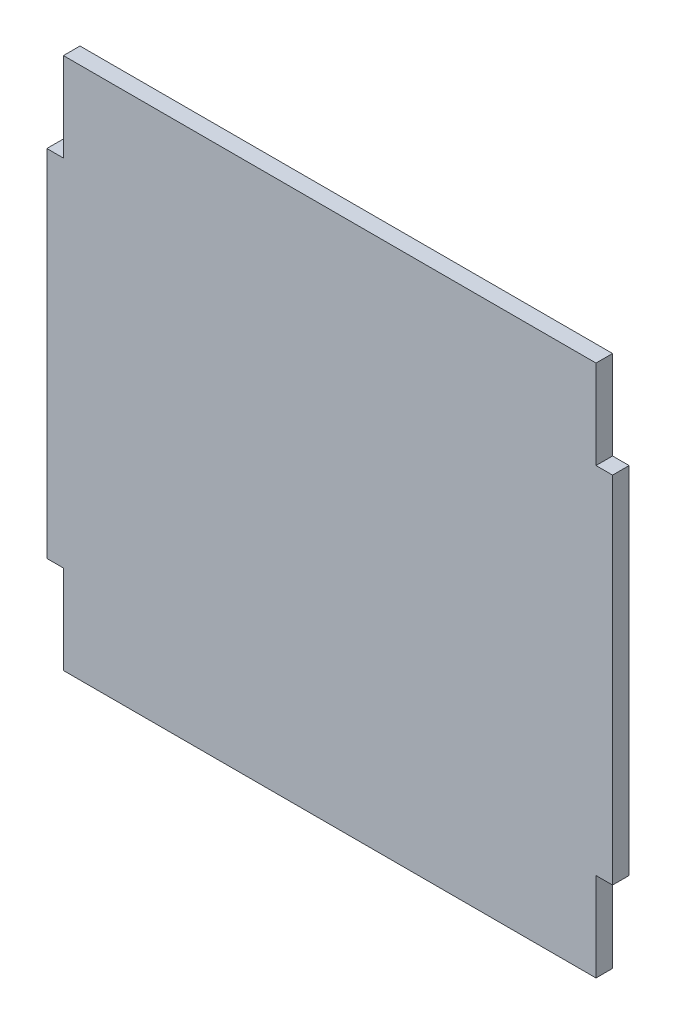
SolidWorks part; units mm, degrees
material "Фанера"
ref_plane "Front Plane" through (0, 0, 0) normal (0, 0, 1) x (1, 0, 0)
ref_plane "Top Plane" through (0, 0, 0) normal (0, 1, 0) x (1, 0, 0)
ref_plane "Right Plane" through (0, 0, 0) normal (1, 0, 0) x (0, 0, -1)
sketch "Эскиз1" plane through (0, 0, 0) normal (0, 0, 1) x (1, 0, 0)
  line L0 (0, 61.2964) -> (0, -70.3102) construction
  line L5 (-45, -45) -> (45, -45)
  line L6 (-45, -45) -> (-45, -30)
  line L7 (-45, 45) -> (45, 45)
  line L8 (45, -45) -> (45, -30)
  line L9 (-45, -45) -> (45, 45) construction
  line L10 (-45, 45) -> (45, -45) construction
  line L15 (-45, -30) -> (-47.8, -30)
  line L17 (-45, 30) -> (-47.8, 30)
  line L18 (-47.8, -30) -> (-47.8, 30)
  line L19 (-45, 0) -> (-47.8, 30) construction
  line L20 (-45, 0) -> (-47.8, -30) construction
  line L21 (-45, 30) -> (-45, 45)
  line L22 (45, -30) -> (47.8, -30)
  line L23 (47.8, -30) -> (47.8, 30)
  line L24 (45, 30) -> (47.8, 30)
  line L25 (45, 30) -> (45, 45)
  point P0 (0, 0)
  point P5 (-45, 0)
  point P8 (0, 0)
  point P15 (-47.8, 0)
  dimension "D3" = 2.8
  dimension "D1" = 90
  dimension "D2" = 30
  dimension "D4" = 90
extrude "Бобышка-Вытянуть1" add sketch "Эскиз1" along normal mid plane 2.8
